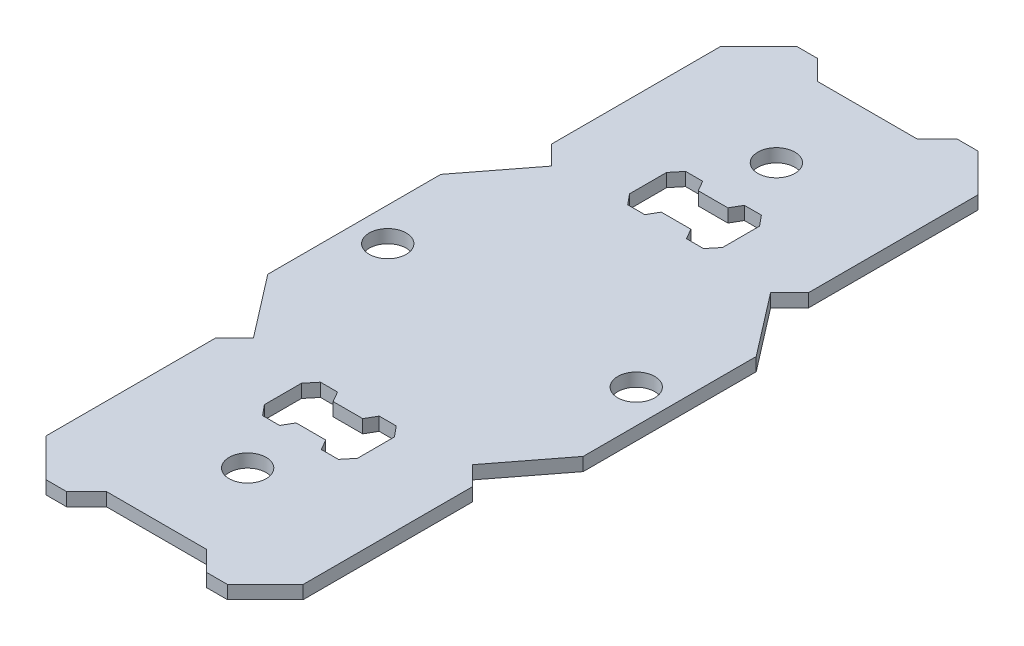
SolidWorks part; units mm, degrees
ref_plane "Front Plane" through (0, 0, 0) normal (0, 0, 1) x (1, 0, 0)
ref_plane "Top Plane" through (0, 0, 0) normal (0, 1, 0) x (1, 0, 0)
ref_plane "Right Plane" through (0, 0, 0) normal (1, 0, 0) x (0, 0, -1)
sketch "Sketch1" plane through (0, 0, 0) normal (0, 1, 0) x (1, 0, 0)
  line L0 (0, 0) -> (640, 0) construction
  line L1 (0, 0) -> (591.2829, 244.9174)
  line L2 (0, 0) -> (591.2829, -244.9174)
  line L3 (0, 0) -> (244.9174, -591.2829)
  line L4 (0, 0) -> (-244.9174, -591.2829)
  line L5 (0, 0) -> (-591.2829, -244.9174)
  line L6 (0, 0) -> (-591.2829, 244.9174)
  line L7 (0, 0) -> (-244.9174, 591.2829)
  line L8 (0, 0) -> (244.9174, 591.2829)
  line L9 (0, 145) -> (55, 145) construction
  line L10 (0, 0) -> (100, 0) construction
  line L11 (0, 0) -> (0, 145) construction
  line L14 (100, 0) -> (100, 145) construction
  circle A0 centre (0, 0) radius 640 construction
  point P15 (0, 0)
  dimension "D1" = 1280
  dimension "D2" = 22.5
  dimension "D4" = 145
  dimension "D5" = 100
  dimension "D6" = 55
  dimension "D3" = 8
sketch "Sketch2" plane through (0, 0, 0) normal (0, 1, 0) x (1, 0, 0)
  line L0 (-486.9956, 169.5033) -> (-66.9956, 169.5033) construction
  line L1 (-188.7141, -86.1278) -> (-188.7141, 241.8722) construction
  line L2 (35.8973, -106.7095) -> (35.8973, 221.2905) construction
sketch "Sketch3" plane through (0, 0, 0) normal (0, 1, 0) x (1, 0, 0)
  line L0 (0, 0) -> (39.7339, 0) construction
  line L1 (0, 0) -> (0, 82.2019) construction
  line L2 (-9.4598, 67.2087) -> (9.4598, 67.2087)
  line L3 (9.4598, 67.2087) -> (13.2319, 70.9808)
  line L4 (13.2319, 70.9808) -> (17.1549, 70.9808)
  line L5 (17.1549, 70.9808) -> (24.3219, 63.8139)
  line L6 (24.3219, 63.8139) -> (24.3219, 31.751)
  line L7 (24.3219, 31.751) -> (20.7384, 28.1675)
  line L8 (20.7384, 28.1675) -> (29.8292, 16.3608)
  line L9 (29.8292, 16.3608) -> (29.8292, -16.3608)
  line L10 (20.7384, -28.1675) -> (29.8292, -16.3608)
  line L11 (24.3219, -31.751) -> (20.7384, -28.1675)
  line L12 (24.3219, -63.8139) -> (24.3219, -31.751)
  line L13 (17.1549, -70.9808) -> (24.3219, -63.8139)
  line L14 (13.2319, -70.9808) -> (17.1549, -70.9808)
  line L15 (9.4598, -67.2087) -> (13.2319, -70.9808)
  line L16 (-9.4598, -67.2087) -> (9.4598, -67.2087)
  line L17 (-9.4598, -67.2087) -> (-13.2319, -70.9808)
  line L18 (-13.2319, -70.9808) -> (-17.1549, -70.9808)
  line L19 (-17.1549, -70.9808) -> (-24.3219, -63.8139)
  line L20 (-24.3219, -63.8139) -> (-24.3219, -31.751)
  line L21 (-24.3219, -31.751) -> (-20.7384, -28.1675)
  line L22 (-20.7384, -28.1675) -> (-29.8292, -16.3608)
  line L23 (-29.8292, 16.3608) -> (-29.8292, -16.3608)
  line L24 (-20.7384, 28.1675) -> (-29.8292, 16.3608)
  line L25 (-24.3219, 31.751) -> (-20.7384, 28.1675)
  line L26 (-24.3219, 63.8139) -> (-24.3219, 31.751)
  line L27 (-17.1549, 70.9808) -> (-24.3219, 63.8139)
  line L28 (-13.2319, 70.9808) -> (-17.1549, 70.9808)
  line L29 (-9.4598, 67.2087) -> (-13.2319, 70.9808)
  line L30 (-2.7999, 38.0281) -> (2.7999, 38.0281)
  line L31 (7.1699, 29.0535) -> (8.7953, 31.0281)
  line L32 (2.7999, 38.0281) -> (3.9418, 40.0027)
  line L33 (3.9418, 40.0027) -> (7.1699, 40.0027)
  line L34 (7.1699, 40.0027) -> (8.7953, 38.0281)
  line L35 (8.7953, 38.0281) -> (8.7953, 31.0281)
  line L36 (0, 34.5281) -> (12.8476, 34.5281) construction
  line L37 (3.9418, 29.0535) -> (7.1699, 29.0535)
  line L38 (2.7999, 31.0281) -> (3.9418, 29.0535)
  line L39 (-2.7999, 31.0281) -> (2.7999, 31.0281)
  line L40 (-2.7999, 31.0281) -> (-3.9418, 29.0535)
  line L41 (-3.9418, 29.0535) -> (-7.1699, 29.0535)
  line L42 (-7.1699, 29.0535) -> (-8.7953, 31.0281)
  line L43 (-8.7953, 38.0281) -> (-8.7953, 31.0281)
  line L44 (-7.1699, 40.0027) -> (-8.7953, 38.0281)
  line L45 (-3.9418, 40.0027) -> (-7.1699, 40.0027)
  line L46 (-2.7999, 38.0281) -> (-3.9418, 40.0027)
  line L47 (-2.7999, -31.0281) -> (-3.9418, -29.0535)
  line L48 (-3.9418, -29.0535) -> (-7.1699, -29.0535)
  line L49 (-7.1699, -29.0535) -> (-8.7953, -31.0281)
  line L50 (-8.7953, -38.0281) -> (-8.7953, -31.0281)
  line L51 (-7.1699, -40.0027) -> (-8.7953, -38.0281)
  line L52 (-2.7999, -38.0281) -> (-3.9418, -40.0027)
  line L53 (-2.7999, -38.0281) -> (2.7999, -38.0281)
  line L54 (2.7999, -38.0281) -> (3.9418, -40.0027)
  line L55 (3.9418, -40.0027) -> (7.1699, -40.0027)
  line L56 (7.1699, -40.0027) -> (8.7953, -38.0281)
  line L57 (8.7953, -38.0281) -> (8.7953, -31.0281)
  line L58 (7.1699, -29.0535) -> (8.7953, -31.0281)
  line L59 (3.9418, -29.0535) -> (7.1699, -29.0535)
  line L60 (2.7999, -31.0281) -> (3.9418, -29.0535)
  line L61 (-2.7999, -31.0281) -> (2.7999, -31.0281)
  line L62 (-3.9418, -40.0027) -> (-7.1699, -40.0027)
  circle A0 centre (23.5, 0) radius 3.5
  circle A1 centre (-23.5, 0) radius 3.5
  circle A2 centre (0, 50) radius 3.5
  circle A3 centre (0, -50) radius 3.5
  point P14 (29.8292, 0)
  point P21 (-29.8292, 0)
  point P23 (0, -67.2087)
  point P36 (0, 67.2087)
  point P44 (8.7953, 34.5281)
  point P50 (0, 31.0281)
  point P57 (0, 38.0281)
  dimension "D3" = 7
  dimension "D4" = 7
  dimension "D1" = 3.5
  dimension "D2" = 23.5
  dimension "D5" = 50
extrude "Boss-Extrude1" add sketch "Sketch3" along normal blind 2.5
